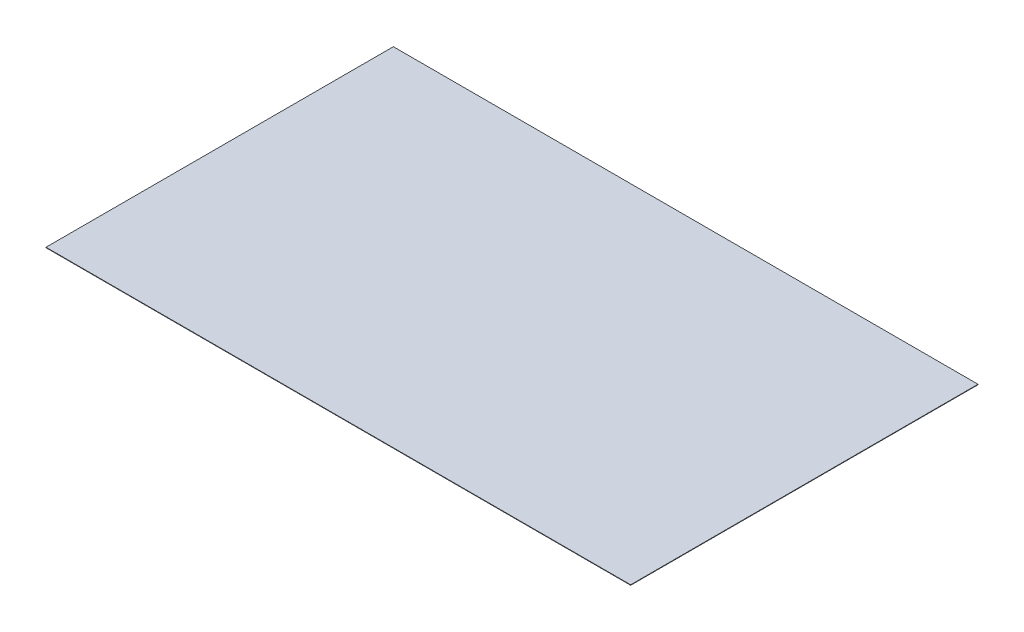
SolidWorks part; units mm, degrees
ref_plane "Front Plane" through (0, 0, 0) normal (0, 0, 1) x (1, 0, 0)
ref_plane "Top Plane" through (0, 0, 0) normal (0, 1, 0) x (1, 0, 0)
ref_plane "Right Plane" through (0, 0, 0) normal (1, 0, 0) x (0, 0, -1)
other "Configuration Table"
sketch "Sketch1" plane through (0, 0, 0) normal (0, 0, 1) x (1, 0, 0)
  line L1 (62.5, 1610) -> (1337.5, 1610)
  line L2 (62.5, 1610) -> (62.5, 1611)
  line L3 (62.5, 1611) -> (1337.5, 1611)
  line L4 (1337.5, 1610) -> (1337.5, 1611)
extrude "STORE_ic_tavan_1" add sketch "Sketch1" against normal blind 757.5 separate body
